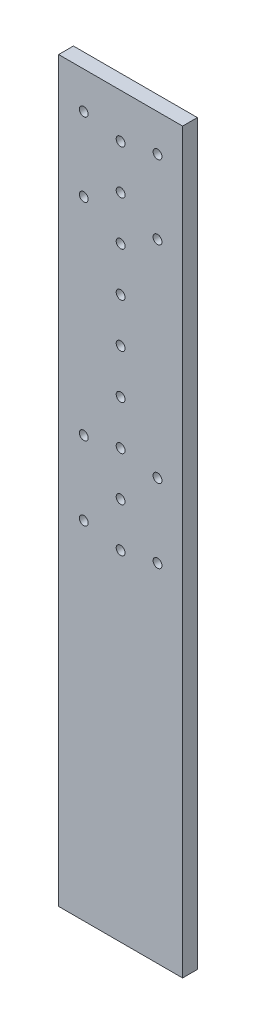
SolidWorks part; units mm, degrees
ref_plane "Front Plane" through (0, 0, 0) normal (0, 0, 1) x (1, 0, 0)
ref_plane "Top Plane" through (0, 0, 0) normal (0, 1, 0) x (1, 0, 0)
ref_plane "Right Plane" through (0, 0, 0) normal (1, 0, 0) x (0, 0, -1)
sketch "Sketch1" plane through (0, 0, 0) normal (0, 0, 1) x (1, 0, 0)
  line L1 (0, 0) -> (42, 0)
  line L2 (0, 0) -> (0, 250)
  line L3 (0, 250) -> (42, 250)
  line L4 (42, 0) -> (42, 250)
  dimension "D1" = 42
  dimension "D2" = 250
extrude "Boss-Extrude1" add sketch "Sketch1" along normal blind 5
sketch "Sketch2" plane through (0, 0, 5) normal (0, 0, 1) x (1, 0, 0)
  line L0 (21, 250) -> (21, 0) construction
  line L1 (42, 250) -> (0, 250) construction
  line L2 (0, 0) -> (42, 0) construction
  line L3 (21, 235) -> (21, 220) construction
  line L5 (8.5, 237.5) -> (33.5, 237.5) construction
  line L6 (8.5, 237.5) -> (8.5, 212.5) construction
  line L7 (8.5, 212.5) -> (33.5, 212.5) construction
  line L8 (33.5, 237.5) -> (33.5, 212.5) construction
  line L9 (8.5, 237.5) -> (33.5, 212.5) construction
  line L10 (8.5, 212.5) -> (33.5, 237.5) construction
  line L11 (8.5, 117.5) -> (33.5, 117.5) construction
  line L12 (8.5, 117.5) -> (8.5, 142.5) construction
  line L13 (8.5, 142.5) -> (33.5, 142.5) construction
  line L14 (33.5, 117.5) -> (33.5, 142.5) construction
  line L15 (8.5, 117.5) -> (33.5, 142.5) construction
  line L16 (8.5, 142.5) -> (33.5, 117.5) construction
  circle A0 centre (21, 235) radius 1.5
  circle A1 centre (21, 220) radius 1.5
  circle A2 centre (21, 205) radius 1.5
  circle A3 centre (21, 190) radius 1.5
  circle A4 centre (21, 175) radius 1.5
  circle A5 centre (21, 160) radius 1.5
  circle A6 centre (21, 145) radius 1.5
  circle A7 centre (21, 130) radius 1.5
  circle A8 centre (21, 115) radius 1.5
  circle A10 centre (8.5, 237.5) radius 1.5
  circle A11 centre (33.5, 237.5) radius 1.5
  circle A12 centre (33.5, 212.5) radius 1.5
  circle A13 centre (8.5, 212.5) radius 1.5
  circle A14 centre (8.5, 142.5) radius 1.5
  circle A15 centre (33.5, 142.5) radius 1.5
  circle A16 centre (33.5, 117.5) radius 1.5
  circle A17 centre (8.5, 117.5) radius 1.5
  point P8 (21, 225)
  point P37 (21, 130)
  dimension "D1" = 15
  dimension "D2" = 3
  dimension "D8" = 3
  dimension "D4" = 15
  dimension "D5" = 12.5
  dimension "D6" = 25
  dimension "D7" = 25
  dimension "D9" = 120
  dimension "D3" = 9
extrude "Cut-Extrude1" cut sketch "Sketch2" against normal through all
